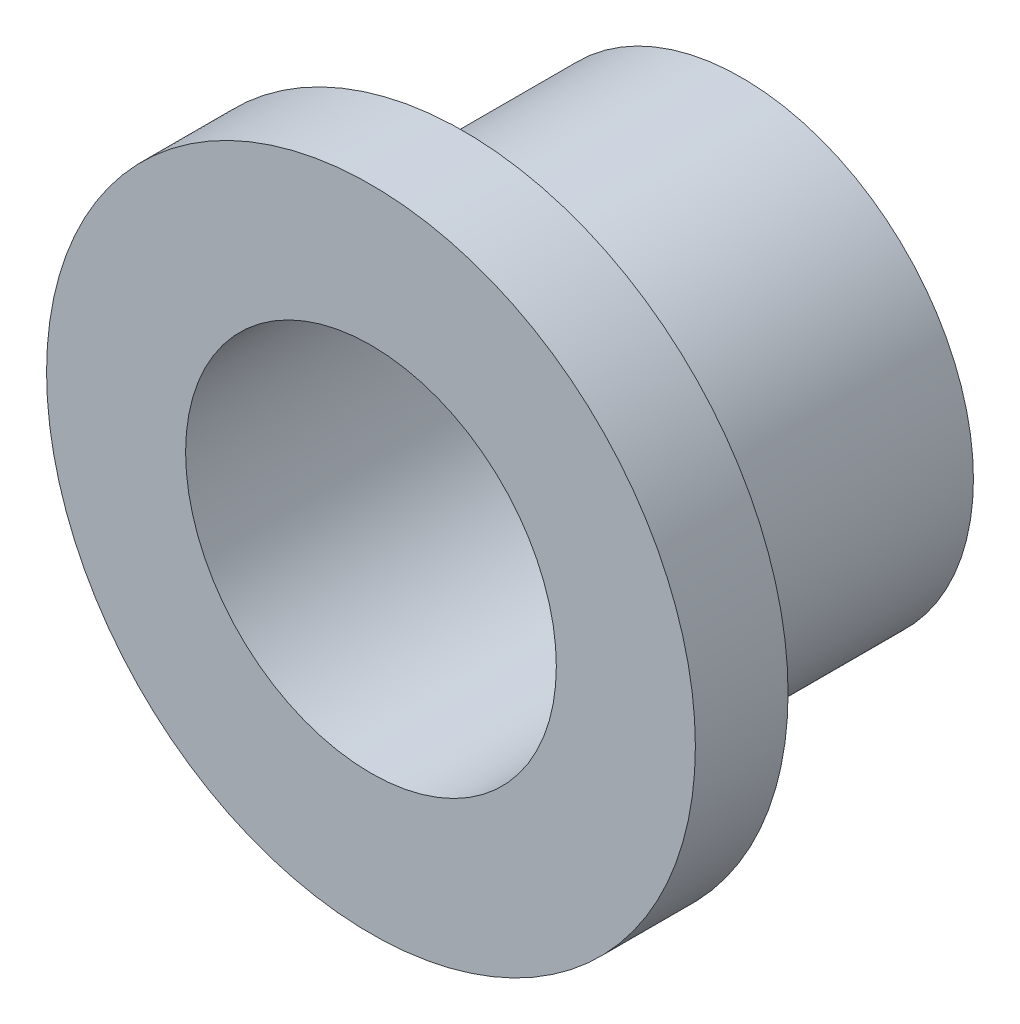
SolidWorks part; units mm, degrees
material "Manganese Bronze"
ref_plane "Front Plane" through (0, 0, 0) normal (0, 0, 1) x (1, 0, 0)
ref_plane "Top Plane" through (0, 0, 0) normal (0, 1, 0) x (1, 0, 0)
ref_plane "Right Plane" through (0, 0, 0) normal (1, 0, 0) x (0, 0, -1)
sketch "Sketch1" plane through (0, 0, 0) normal (1, 0, 0) x (0, 0, -1)
  line L0 (0, 6.35) -> (0, 11.1125)
  line L1 (0, 11.1125) -> (3.175, 11.1125)
  line L2 (3.175, 11.1125) -> (3.175, 7.9375)
  line L3 (3.175, 7.9375) -> (12.7, 7.9375)
  line L4 (12.7, 7.9375) -> (12.7, 6.35)
  line L5 (12.7, 6.35) -> (0, 6.35)
  line L6 (0, 0) -> (50000, 0) construction
  dimension "D1" = 12.7
  dimension "D2" = 15.875
  dimension "D3" = 22.225
  dimension "D4" = 3.175
  dimension "D5" = 9.525
revolve "Revolve1" add sketch "Sketch1" angle 360 about L6
